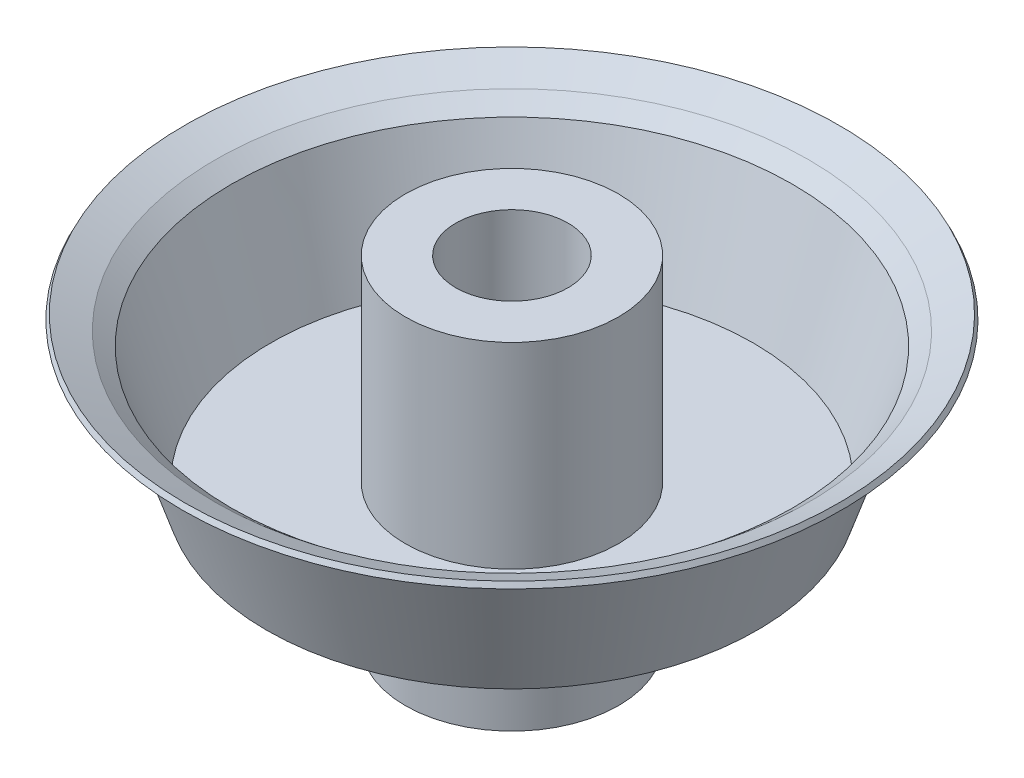
SolidWorks part; units mm, degrees
ref_plane "Спереди" through (0, 0, 0) normal (0, 0, 1) x (1, 0, 0)
ref_plane "Сверху" through (0, 0, 0) normal (0, 1, 0) x (1, 0, 0)
ref_plane "Справа" through (0, 0, 0) normal (1, 0, 0) x (0, 0, -1)
sketch "Эскиз1" plane through (0, 0, 0) normal (0, 0, 1) x (1, 0, 0)
  line L0 (0, 0) -> (0, -32.1034) construction
  line L1 (-5.6001, 0) -> (69.589, 0) construction
  line L2 (19, 0) -> (43, 0)
  line L3 (52.8896, 23.3322) -> (58.3028, 25.953)
  line L4 (50, 21) -> (43, 0)
  line L5 (50, 21) -> (52.8896, 23.3322)
revolve "Повернуть-Тонкостенный1" add sketch "Эскиз1" angle 360 about L0
sketch "Эскиз3" plane through (0, 0, 0) normal (0, 1, 0) x (1, 0, 0)
  circle A0 centre (0, 0) radius 19
  circle A1 centre (0, 0) radius 10
  dimension "D1" = 20
  dimension "D2" = 38
extrude "Вытянуть10" add sketch "Эскиз3" against normal blind 25 and the other way blind 35
